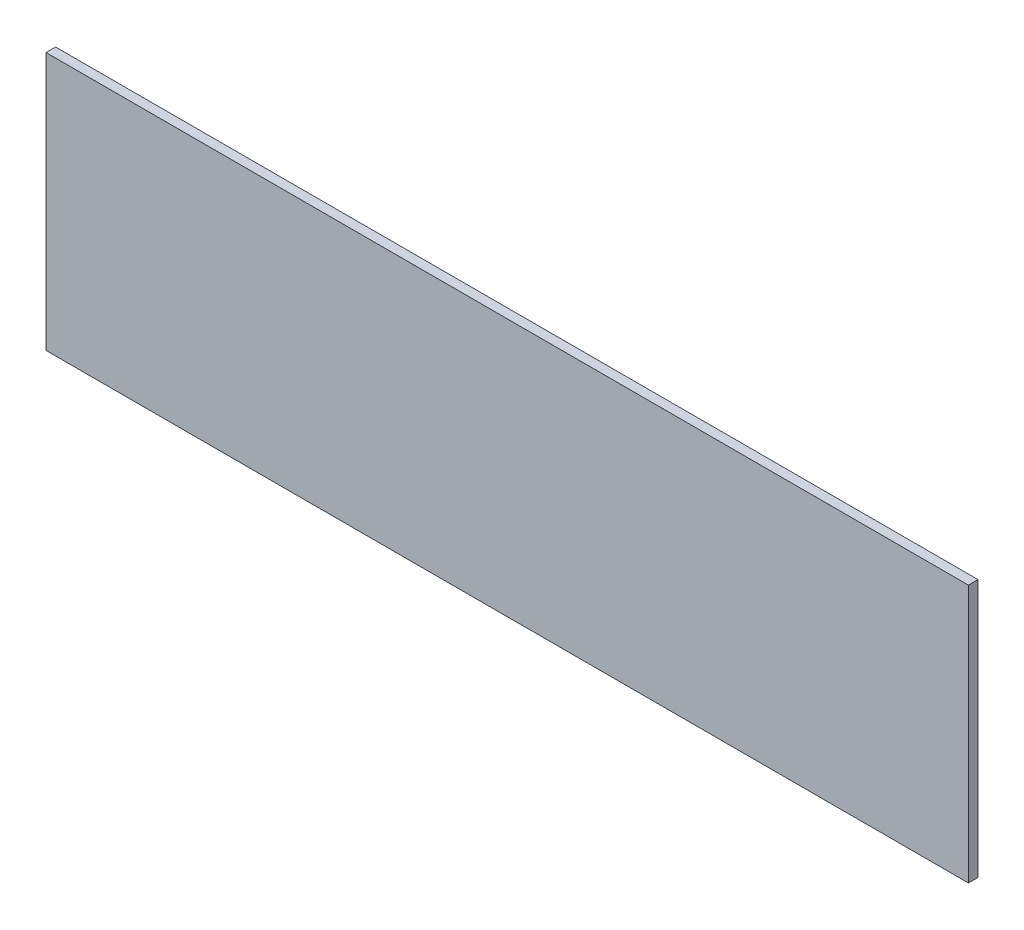
SolidWorks part; units mm, degrees
material "ABS"
ref_plane "X-Y Datum" through (0, 0, 0) normal (0, 0, 1) x (1, 0, 0)
ref_plane "X-Z Datum" through (0, 0, 0) normal (0, 1, 0) x (1, 0, 0)
ref_plane "Y-Z Datum" through (0, 0, 0) normal (1, 0, 0) x (0, 0, -1)
sketch "Sketch1" plane through (0, 0, 0) normal (0, 0, 1) x (1, 0, 0)
  line L1 (-153.025, 42.8) -> (153.025, 42.8)
  line L2 (-153.025, 42.8) -> (-153.025, -42.8)
  line L3 (-153.025, -42.8) -> (153.025, -42.8)
  line L4 (153.025, 42.8) -> (153.025, -42.8)
  line L5 (-153.025, 42.8) -> (153.025, -42.8) construction
  line L6 (-153.025, -42.8) -> (153.025, 42.8) construction
  point P0 (0, 0)
  dimension "D1" = 85.6
  dimension "D2" = 306.05
extrude "Boss-Extrude1" add sketch "Sketch1" along normal blind 3.175
